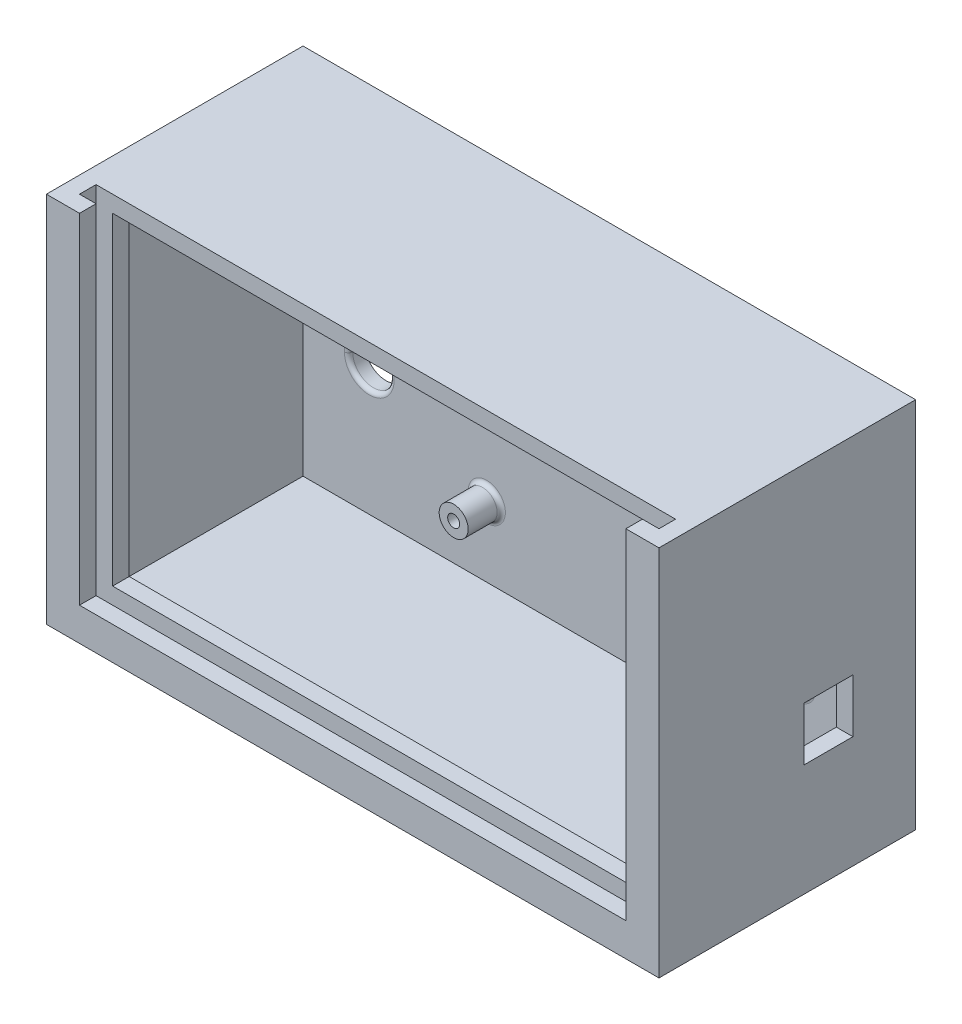
SolidWorks part; units mm, degrees
ref_plane "Front Plane" through (0, 0, 0) normal (0, 0, 1) x (1, 0, 0)
ref_plane "Top Plane" through (0, 0, 0) normal (0, 1, 0) x (1, 0, 0)
ref_plane "Right Plane" through (0, 0, 0) normal (1, 0, 0) x (0, 0, -1)
sketch "Sketch1" plane through (0, 0, 0) normal (0, 0, 1) x (1, 0, 0)
  line L1 (-74, -45) -> (74, -45)
  line L2 (-74, -45) -> (-74, 45)
  line L3 (-74, 45) -> (74, 45)
  line L4 (74, -45) -> (74, 45)
  line L5 (-74, -45) -> (74, 45) construction
  line L6 (-74, 45) -> (74, -45) construction
  point P0 (0, 0)
  dimension "D1" = 148
  dimension "D2" = 90
extrude "Boss-Extrude1" add sketch "Sketch1" along normal blind 4
sketch "Sketch2" plane through (0, 0, 4) normal (0, 0, 1) x (1, 0, 0)
  line L0 (74, -45) -> (74, 45) construction
  circle A0 centre (54, 0) radius 4
  circle A1 centre (14, 0) radius 4
  point P6 (0, 0)
  point P7 (0, 0)
  dimension "D1" = 8
  dimension "D2" = 8
  dimension "D3" = 40
  dimension "D4" = 20
extrude "Cut-Extrude1" cut sketch "Sketch2" against normal blind 4
sketch "Sketch3" plane through (0, 0, 4) normal (0, 0, 1) x (1, 0, 0)
  circle A0 centre (-33.0986, 24.1681) radius 1.45
  circle A1 centre (49.5276, 24.1681) radius 1.45
  circle A2 centre (49.5276, -24.1681) radius 1.45
  circle A3 centre (-25.6056, -24.1681) radius 1.45
  circle A4 centre (-33.0986, 24.1681) radius 3.5
  circle A5 centre (49.5276, 24.1681) radius 3.5
  circle A6 centre (-25.6056, -24.1681) radius 3.5
  circle A7 centre (49.5276, -24.1681) radius 3.2199
  dimension "D1" = 2.9
  dimension "D2" = 2.9
  dimension "D3" = 2.9
  dimension "D4" = 2.9
  dimension "D5" = 7
  dimension "D6" = 7
  dimension "D7" = 7
  dimension "D8" = 6.4399
extrude "Boss-Extrude2" add sketch "Sketch3" along normal blind 8
sketch "Sketch7" plane through (0, 0, 4) normal (0, 0, 1) x (1, 0, 0)
  line L0 (-54, -10) -> (-54, 10) construction
  line L1 (-59, -10) -> (-59, 10)
  line L2 (-49, -10) -> (-49, 10)
  line L3 (-74, 45) -> (-74, -45) construction
  arc A0 (-59, -10) -> (-49, -10) centre (-54, -10) ccw
  arc A1 (-49, 10) -> (-59, 10) centre (-54, 10) ccw
  point P2 (-54, 0)
  point P9 (-50, -11.0276)
  point P10 (0, 0)
  dimension "D1" = 20
  dimension "D2" = 10
  dimension "D3" = 20
extrude "Cut-Extrude2" cut sketch "Sketch7" against normal blind 10
sketch "Sketch8" plane through (0, 0, 4) normal (0, 0, 1) x (1, 0, 0)
  line L0 (-70, 41) -> (70, 41)
  line L1 (-74, -45) -> (74, -45)
  line L2 (-74, -45) -> (-74, 45)
  line L3 (-74, 45) -> (74, 45)
  line L4 (74, -45) -> (74, 45)
  line L5 (-74, -45) -> (74, 45) construction
  line L6 (-74, 45) -> (74, -45) construction
  line L7 (70, -41) -> (70, 41)
  line L8 (-70, -41) -> (70, -41)
  line L9 (-70, -41) -> (-70, 41)
  point P0 (0, 0)
  dimension "D1" = 4
extrude "Boss-Extrude3" add sketch "Sketch8" along normal blind 50
fillet "Fillet1" radius 1 8 edges at (-54, -15, 4) (-59, 0, 4) (-54, 15, 4) (-49, 0, 4) (-29.1056, -24.1681, 4) (46.3077, -24.1681, 4) (46.0276, 24.1681, 4) (-36.5986, 24.1681, 4)
sketch "Sketch9" plane through (0, 0, 54) normal (0, 0, 1) x (1, 0, 0)
  line L0 (74, 45) -> (-74, 45) construction
  line L1 (-74, 45) -> (-66, 45)
  line L2 (-74, 45) -> (-74, -45)
  line L3 (-74, -45) -> (-66, -45)
  line L4 (-66, 45) -> (-66, -37)
  line L8 (74, 45) -> (66, 45)
  line L9 (74, 45) -> (74, -45)
  line L10 (74, -45) -> (66, -45)
  line L11 (66, 45) -> (66, -37)
  line L12 (-74, 45) -> (-74, -45) construction
  line L13 (-66, -45) -> (66, -45)
  line L15 (-66, -37) -> (66, -37)
  line L17 (74, -45) -> (74, 45) construction
  line L18 (-74, -45) -> (74, -45) construction
  point P6 (0, 0)
  point P7 (0, 0)
  point P18 (0, 0)
  dimension "D1" = 8
  dimension "D2" = 8
  dimension "D3" = 8
extrude "Boss-Extrude4" add sketch "Sketch9" along normal blind 8 and the other way blind 4
sketch "Sketch10" plane through (0, 45, 0) normal (0, 1, 0) x (1, 0, 0)
  line L0 (74, -62) -> (74, 0) construction
  line L1 (-70, -58) -> (70, -58)
  line L2 (-70, -58) -> (-70, -54)
  line L3 (-70, -54) -> (70, -54)
  line L4 (70, -58) -> (70, -54)
  line L5 (-70, -58) -> (70, -54) construction
  line L6 (-70, -54) -> (70, -58) construction
  line L7 (74, -62) -> (66, -62) construction
  point P0 (0, -56)
  point P9 (0, 0)
  dimension "D1" = 4
  dimension "D2" = 4
  dimension "D3" = 4
extrude "Cut-Extrude3" cut sketch "Sketch10" against normal up to surface (86 mm away) up to face at (0, -41, 27)
sketch "Sketch11" plane through (70, 0, 0) normal (-1, 0, 0) x (0, 0, 1)
  line L1 (26.446, -5.4991) -> (15.651, -5.4991) construction
  line L2 (26.446, -5.4991) -> (26.446, -17.4371) construction
  line L3 (26.446, -17.4371) -> (15.651, -17.4371) construction
  line L4 (15.651, -5.4991) -> (15.651, -17.4371) construction
  line L8 (26.946, -4.9991) -> (15.151, -4.9991)
  line L9 (15.151, -4.9991) -> (15.151, -17.9371)
  line L10 (26.946, -17.9371) -> (15.151, -17.9371)
  line L11 (26.946, -4.9991) -> (26.946, -17.9371)
  dimension "D1" = 0.5
extrude "Cut-Extrude4" cut sketch "Sketch11" against normal up to next
